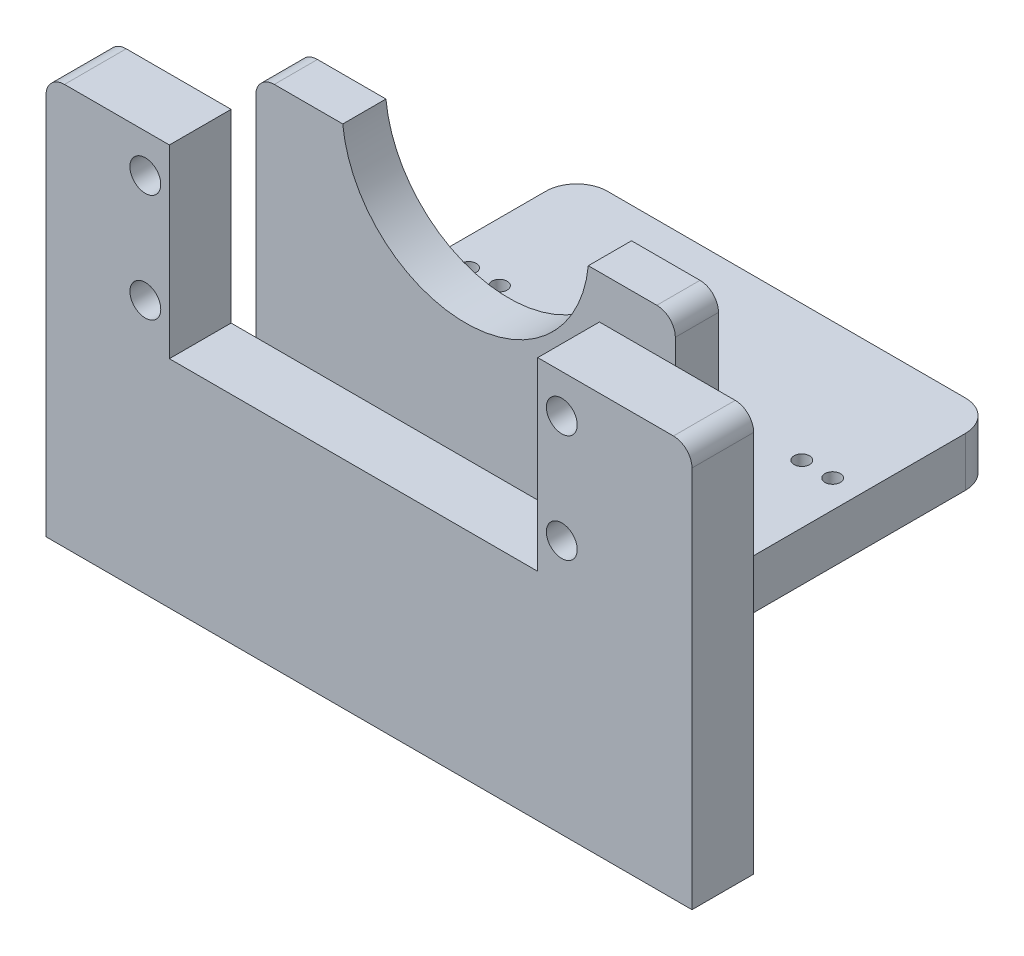
SolidWorks part; units mm, degrees
ref_plane "Alzado" through (0, 0, 0) normal (0, 0, 1) x (1, 0, 0)
ref_plane "Planta" through (0, 0, 0) normal (0, 1, 0) x (1, 0, 0)
ref_plane "Vista lateral" through (0, 0, 0) normal (1, 0, 0) x (0, 0, -1)
sketch "Croquis1" plane through (0, 0, 0) normal (0, 0, 1) x (1, 0, 0)
  line L0 (74.2228, 23.0272) -> (49.2228, 23.0272)
  line L1 (-30.4772, 23.0272) -> (-10.4772, 23.0272)
  line L2 (19.3728, -6.9728) -> (19.3728, 21.0228) construction
  line L3 (-10.4772, -6.9728) -> (49.2228, -6.9728)
  line L6 (-10.4772, 23.0272) -> (46.5185, 23.0272) construction
  line L7 (74.2228, 23.0272) -> (74.2228, -41.9728)
  line L8 (60.3079, -6.9728) -> (-21.5623, -6.9728) construction
  line L9 (74.2228, -41.9728) -> (-30.4772, -41.9728)
  line L10 (-30.4772, -41.9728) -> (-30.4772, 23.0272)
  line L11 (-10.4772, 23.0272) -> (-10.4772, -6.9728)
  line L16 (-16.3754, 8.0272) -> (42.6161, 8.0272) construction
  line L18 (-20, -4.2075) -> (-20, -6.9728)
  line L21 (49.2228, -6.9728) -> (49.2228, 23.0272)
  line L23 (-10.4772, 23.0272) -> (-10.4772, -1.9815) construction
  circle A0 centre (-14.3772, 16.7772) radius 2.5
  circle A1 centre (-14.3772, -0.7228) radius 2.5
  circle A5 centre (53.1228, 16.7772) radius 2.5
  circle A6 centre (53.1228, -0.7228) radius 2.5
  point P5 (-16.3754, 10.5228)
  point P10 (42.6161, 10.5228)
  point P11 (-10.4772, 8.0272)
  point P24 (19.3728, -6.9728)
  point P30 (19.3728, -6.9728)
  point P33 (0, 10.5228)
  point P51 (19.3728, 21.0228)
  dimension "D4" = 59.7
  dimension "D3" = 65
  dimension "D6" = 33.75
  dimension "D5" = 17.5
  dimension "D7" = 30
  dimension "D8" = 5
  dimension "D1" = 25
  dimension "D2" = 20
extrude "Saliente-Extruir2" add sketch "Croquis1" along normal blind 10
sketch "Croquis3" plane through (0, 0, 0) normal (0, 0, -1) x (-1, 0, 0)
  line L0 (30.4772, -41.9728) -> (30.4772, 23.0272) construction
  line L1 (-74.2228, -41.9728) -> (30.4772, -41.9728)
  line L2 (-74.2228, -41.9728) -> (-74.2228, -33.9728)
  line L3 (-74.2228, -33.9728) -> (30.4772, -33.9728)
  line L4 (30.4772, -41.9728) -> (30.4772, -33.9728)
  dimension "D1" = 8
extrude "Saliente-Extruir3" add sketch "Croquis3" along normal blind 45
sketch "Croquis4" plane through (0, -33.9728, 0) normal (0, 1, 0) x (1, 0, 0)
  line L0 (-30.4772, 45) -> (-30.4772, 0) construction
  line L1 (-30.4772, 31) -> (74.2228, 31)
  line L2 (-30.4772, 31) -> (-30.4772, 24)
  line L3 (-30.4772, 24) -> (74.2228, 24)
  line L4 (74.2228, 31) -> (74.2228, 24)
  line L5 (74.2228, 45) -> (74.2228, 0) construction
  line L6 (-30.4772, 0) -> (74.2228, 0) construction
  dimension "D1" = 24
  dimension "D2" = 7
extrude "Saliente-Extruir4" add sketch "Croquis4" along normal blind 40
sketch "Croquis6" plane through (0, 0, -24) normal (0, 0, 1) x (1, 0, 0)
  line L0 (3.5228, 26.6006) -> (3.5228, -36.3864) construction
  line L1 (74.2228, -33.9728) -> (-30.4772, -33.9728) construction
  line L2 (-10.4772, 23.0272) -> (-10.4772, -6.9728) construction
  line L3 (53.1228, -0.7228) -> (53.1228, 16.7772) construction
  line L4 (53.1228, 8.0272) -> (-53.4725, 8.0272) construction
  circle A0 centre (3.5228, 8.0272) radius 20
  point P14 (0, 0)
  dimension "D2" = 40
  dimension "D1" = 14
  dimension "D3" = 42
extrude "Cortar-Extruir1" cut sketch "Croquis6" against normal through all
fillet "Redondeo2" radius 3 2 edges at (74.2228, 23.0272, 5) (-30.4772, 23.0272, 5)
sketch "Croquis10" plane through (0, 6.0272, 0) normal (0, 1, 0) x (1, 0, 0)
  line L0 (74.2228, 45) -> (37.5226, 45)
  line L1 (-30.4772, 45) -> (74.2228, 45) construction
  line L2 (37.5226, 45) -> (37.5226, 15.0522)
  line L3 (37.5226, 15.0522) -> (74.2228, 0)
  line L4 (74.2228, 0) -> (74.2228, 45)
  line L5 (74.2228, 45) -> (74.2228, 31) construction
  line L6 (-16.3769, 31) -> (-16.3769, 24) construction
  line L7 (-30.4772, 31) -> (-30.4772, 24) construction
  line L8 (23.4226, 24) -> (23.4226, 31) construction
  point P12 (-16.3769, 27.5)
  point P15 (-30.4772, 27.5)
  point P18 (23.4226, 27.5)
  dimension "D1" = 14.1003
  dimension "D2" = 14.1
extrude "Cortar-Extruir3" cut sketch "Croquis10" against normal through all
sketch "Croquis12" plane through (0, -33.9728, 0) normal (0, 1, 0) x (1, 0, 0)
  line L0 (37.5226, 31) -> (37.5226, 45) construction
  line L1 (-30.4772, 45) -> (37.5226, 45)
  line L2 (-30.4772, 45) -> (-30.4772, 38)
  line L3 (-30.4772, 38) -> (37.5226, 38)
  line L4 (37.5226, 45) -> (37.5226, 38)
extrude "Cortar-Extruir4" cut sketch "Croquis12" against normal through all
fillet "Redondeo5" radius 5 1 edges at (37.5226, -37.9728, -15.0522)
sketch "Croquis13" plane through (0, 0, -38) normal (0, 0, -1) x (-1, 0, 0)
  line L1 (30.4772, -41.9728) -> (-37.5226, -41.9728) construction
  line L2 (30.4772, -33.9728) -> (-37.5226, -33.9728)
  line L3 (30.4772, -33.9728) -> (30.4772, -41.9728)
  line L4 (30.4772, -41.9728) -> (-37.5226, -41.9728)
  line L5 (-37.5226, -33.9728) -> (-37.5226, -41.9728)
  line L6 (30.4772, -33.9728) -> (-37.5226, -41.9728) construction
  line L7 (30.4772, -41.9728) -> (-37.5226, -33.9728) construction
  line L8 (30.4772, -33.9728) -> (-37.5226, -33.9728) construction
  line L9 (30.4772, -41.9728) -> (30.4772, -33.9728) construction
  line L10 (-37.5226, -41.9728) -> (-37.5226, -33.9728) construction
  point P3 (-3.5227, -37.9728)
extrude "Cortar-Extruir6" cut sketch "Croquis13" against normal up to surface (7 mm away) up to face at (3.5227, -10.3062, -31)
sketch "Croquis18" plane through (0, 0, -31) normal (0, 0, -1) x (-1, 0, 0)
  line L0 (-37.5226, 6.0272) -> (-37.5226, -41.9728) construction
  line L1 (-37.5226, -33.9728) -> (30.4772, -33.9728)
  line L2 (-37.5226, -33.9728) -> (-37.5226, -41.9728)
  line L3 (-37.5226, -41.9728) -> (30.4772, -41.9728)
  line L4 (30.4772, -33.9728) -> (30.4772, -41.9728)
  line L5 (30.4772, -33.9728) -> (-74.2228, -33.9728) construction
extrude "Saliente-Extruir7" add sketch "Croquis18" along normal blind 45
sketch "Croquis19" plane through (0, -33.9728, 0) normal (0, 1, 0) x (1, 0, 0)
  line L0 (-30.4772, 54) -> (37.5228, 54) construction
  line L1 (-30.4772, 76) -> (-30.4772, 31) construction
  line L2 (23.4226, 24) -> (23.4226, 31) construction
  line L3 (23.4226, 27.5) -> (-16.3769, 27.5) construction
  line L6 (3.5228, 27.5) -> (3.5228, 70.8719) construction
  line L7 (-30.4772, 31) -> (37.5226, 31) construction
  line L8 (-16.3769, 31) -> (-16.3769, 24) construction
  circle A0 centre (-25.9772, 54) radius 1.25
  circle A1 centre (33.0228, 54) radius 1.25
  circle A2 centre (-20.9772, 54) radius 1.25
  circle A3 centre (28.0228, 54) radius 1.25
  circle A4 centre (3.5228, 54) radius 6.5
  point P24 (3.5228, 54)
  point P28 (23.4226, 27.5)
  point P30 (-16.3769, 27.5)
  dimension "D2" = 2.5
  dimension "D3" = 49
  dimension "D6" = 13
  dimension "D1" = 23
  dimension "D4" = 59
extrude "Cortar-Extruir7" cut sketch "Croquis19" against normal up to next
fillet "Redondeo8" radius 5 2 edges at (-30.4772, -37.9728, -76) (37.5226, -37.9728, -76)
fillet "Redondeo10" radius 3 2 edges at (-30.4772, 6.0272, -27.5) (37.5226, 6.0272, -27.5)
